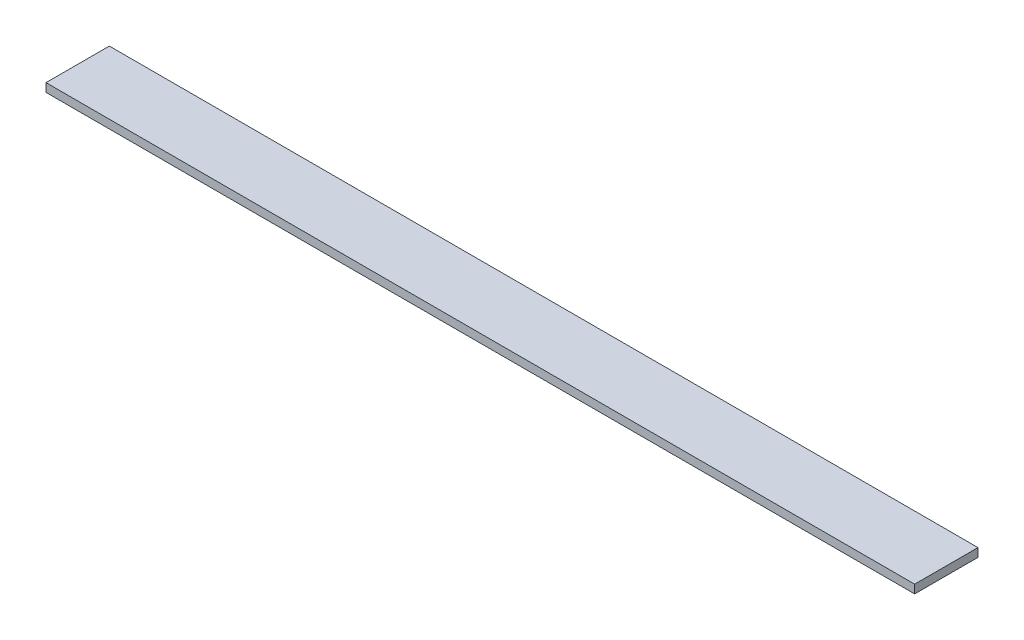
SolidWorks part; units mm, degrees
material "Pine"
ref_plane "Front Plane" through (0, 0, 0) normal (0, 0, 1) x (1, 0, 0)
ref_plane "Top Plane" through (0, 0, 0) normal (0, 1, 0) x (1, 0, 0)
ref_plane "Right Plane" through (0, 0, 0) normal (1, 0, 0) x (0, 0, -1)
sketch "Sketch1" plane through (0, 0, 0) normal (0, 1, 0) x (1, 0, 0)
  line L1 (-609.6, -44.45) -> (609.6, -44.45)
  line L2 (-609.6, -44.45) -> (-609.6, 44.45)
  line L3 (-609.6, 44.45) -> (609.6, 44.45)
  line L4 (609.6, -44.45) -> (609.6, 44.45)
  line L5 (-609.6, -44.45) -> (609.6, 44.45) construction
  line L6 (-609.6, 44.45) -> (609.6, -44.45) construction
  point P0 (0, 0)
  dimension "D1" = 88.9
  dimension "D2" = 1219.2
extrude "Boss-Extrude1" add sketch "Sketch1" along normal mid plane 11.9062
